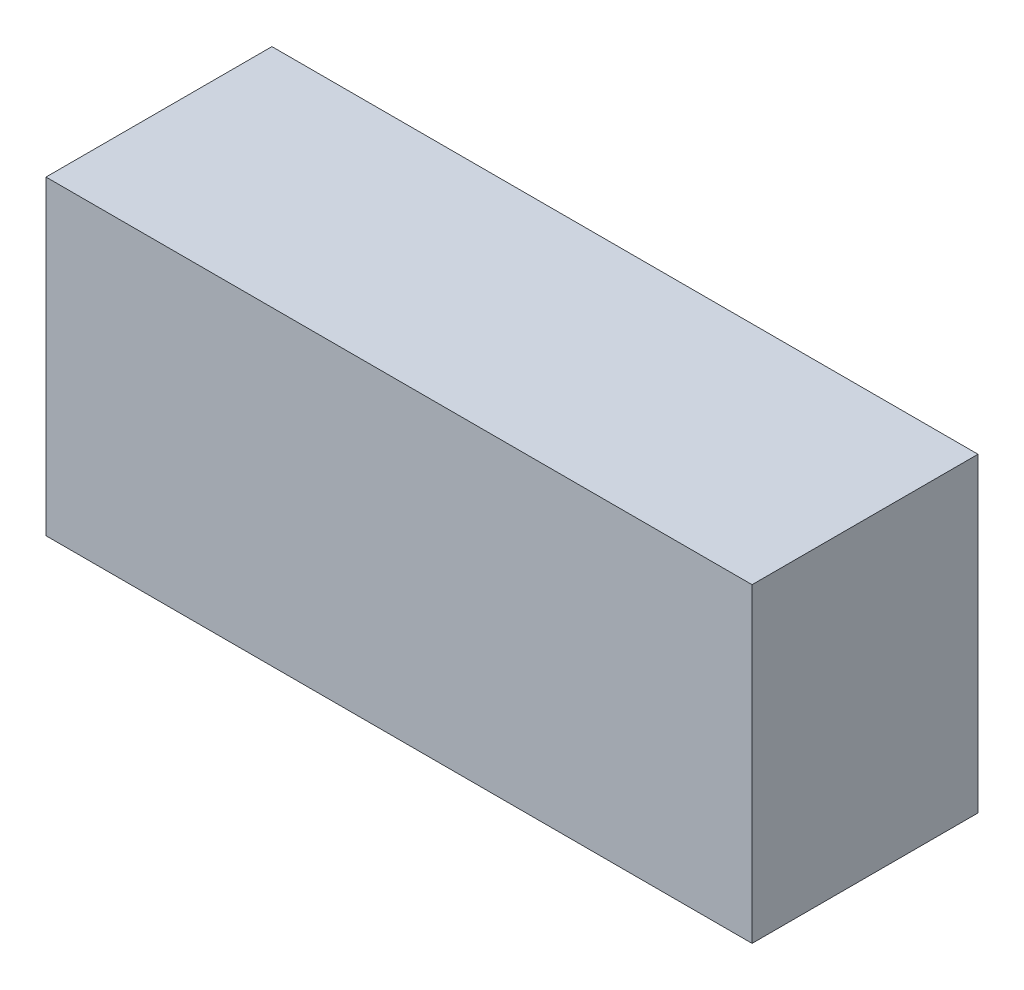
SolidWorks part; units mm, degrees
ref_plane "Front Plane" through (0, 0, 0) normal (0, 0, 1) x (1, 0, 0)
ref_plane "Top Plane" through (0, 0, 0) normal (0, 1, 0) x (1, 0, 0)
ref_plane "Right Plane" through (0, 0, 0) normal (1, 0, 0) x (0, 0, -1)
sketch "Sketch1" plane through (0, 0, 0) normal (0, 0, 1) x (1, 0, 0)
  line L1 (-25, -11) -> (25, -11)
  line L2 (-25, -11) -> (-25, 11)
  line L3 (-25, 11) -> (25, 11)
  line L4 (25, -11) -> (25, 11)
extrude "REFERENCE_ENVELOPE_NOT_MANUFACTURING" add sketch "Sketch1" along normal blind 16 from offset 0
